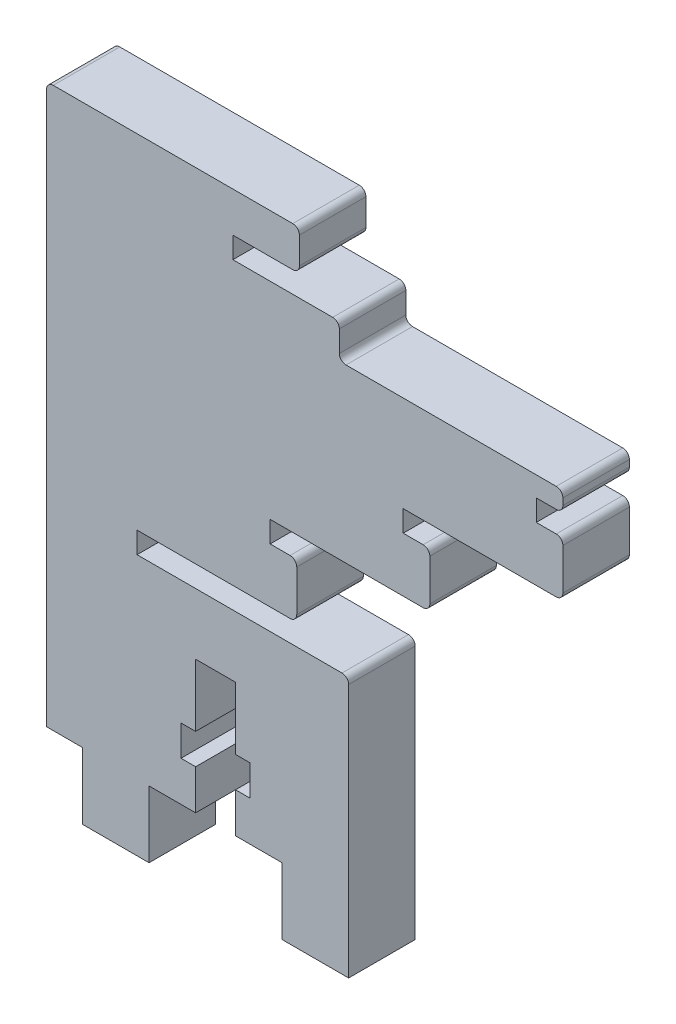
SolidWorks part; units mm, degrees
ref_plane "Front Plane" through (0, 0, 0) normal (0, 0, 1) x (1, 0, 0)
ref_plane "Top Plane" through (0, 0, 0) normal (0, 1, 0) x (1, 0, 0)
ref_plane "Right Plane" through (0, 0, 0) normal (1, 0, 0) x (0, 0, -1)
sketch "Sketch1" plane through (0, 0, 0) normal (0, 0, 1) x (1, 0, 0)
  line L1 (20, 5) -> (20, 19.6) construction
  line L3 (14.1, 25.3) -> (14.1, 26.9)
  line L4 (14.1, 26.9) -> (26.1, 26.9)
  line L5 (26.1, 26.9) -> (26.1, 31)
  line L8 (10, 5) -> (10, 15.0197) construction
  line L9 (8.5, 5) -> (5, 5)
  line L10 (5, 0) -> (0, 0)
  line L11 (0, 0) -> (0, 5)
  line L12 (5, 0) -> (5, 5)
  line L13 (11.5, 5) -> (15, 5)
  line L14 (15, 5) -> (15, 0)
  line L15 (15, 0) -> (20, 0)
  line L16 (20, 0) -> (20, 5)
  line L17 (8.5, 5) -> (11.5, 5) construction
  line L18 (11.5, 5) -> (11.5, 8)
  line L19 (11.5, 10.3) -> (12.6, 10.3)
  line L20 (7.4, 8) -> (7.4, 10.3)
  line L21 (12.6, 8) -> (11.5, 8)
  line L22 (11.5, 10.3) -> (11.5, 15)
  line L23 (11.5, 15) -> (8.5, 15)
  line L24 (8.5, 15) -> (8.5, 10.3)
  line L25 (8.5, 8) -> (7.4, 8)
  line L26 (12.6, 10.3) -> (12.6, 8)
  line L27 (7.4, 10.3) -> (8.5, 10.3)
  line L28 (8.5, 8) -> (8.5, 5)
  line L29 (10, 15) -> (10, 5) construction
  line L30 (26.1, 31) -> (24.1, 31)
  line L31 (24.1, 31) -> (24.1, 32.6)
  line L32 (24.1, 32.6) -> (36.1, 32.6)
  line L33 (36.1, 32.6) -> (36.1, 36.7)
  line L37 (20, 25.3) -> (20, 5) construction
  line L39 (36.1, 36.7) -> (34.1, 36.7)
  line L40 (34.1, 36.7) -> (34.1, 38.3)
  line L41 (34.1, 38.3) -> (36.1, 38.3)
  line L47 (16.3, 47) -> (-2.7, 47)
  line L49 (36.1, 38.3) -> (36.1, 42.4) construction
  line L50 (36.1, 42.4) -> (11.3, 42.4) construction
  line L51 (11.3, 42.4) -> (11.3, 44)
  line L52 (11.3, 44) -> (16.3, 44)
  line L53 (16.3, 44) -> (16.3, 47)
  line L54 (14.1, 25.3) -> (20, 25.3) construction
  line L55 (36.1, 38.3) -> (36.1, 39.8)
  line L56 (36.1, 39.8) -> (19.3, 39.8)
  line L57 (19.3, 39.8) -> (19.3, 42.4)
  line L58 (19.3, 42.4) -> (11.3, 42.4)
  line L59 (0, 5) -> (-2.7, 5)
  line L60 (-2.7, 5) -> (-2.7, 47)
  line L61 (14.1, 25.3) -> (16.1, 25.3)
  line L62 (16.1, 25.3) -> (16.1, 21.2)
  line L63 (16.1, 21.2) -> (4.1, 21.2)
  line L64 (4.1, 21.2) -> (4.1, 19.6)
  line L65 (4.1, 19.6) -> (20, 19.6)
  line L66 (20, 19.6) -> (20, 5)
  dimension "D3" = 12
  dimension "D4" = 5.7
  dimension "D5" = 10
  dimension "D6" = 5
  dimension "D7" = 5
  dimension "D8" = 5.2
  dimension "D9" = 3
  dimension "D10" = 2.3
  dimension "D11" = 3
  dimension "D12" = 10
  dimension "D13" = 14
  dimension "D14" = 10
  dimension "D15" = 5
  dimension "D16" = 1.6
  dimension "D18" = 5.7
  dimension "D19" = 3
  dimension "D20" = 22.8
  dimension "D21" = 2.6
  dimension "D22" = 8
  dimension "D23" = 2.7
  dimension "D24" = 5.7
  dimension "D25" = 20.3
  dimension "D26" = 10
extrude "Boss-Extrude1" add sketch "Sketch1" along normal blind 5
fillet "Fillet3" radius 0.5 14 edges at (26.1, 26.9, 2.5) (16.3, 44, 2.5) (16.3, 47, 2.5) (36.1, 32.6, 2.5) (36.1, 36.7, 2.5) (26.1, 31, 2.5) (36.1, 38.3, 2.5) (36.1, 39.8, 2.5) (19.3, 39.8, 2.5) (19.3, 42.4, 2.5) (-2.7, 47, 2.5) (20, 19.6, 2.5) (16.1, 21.2, 2.5) (16.1, 25.3, 2.5)
